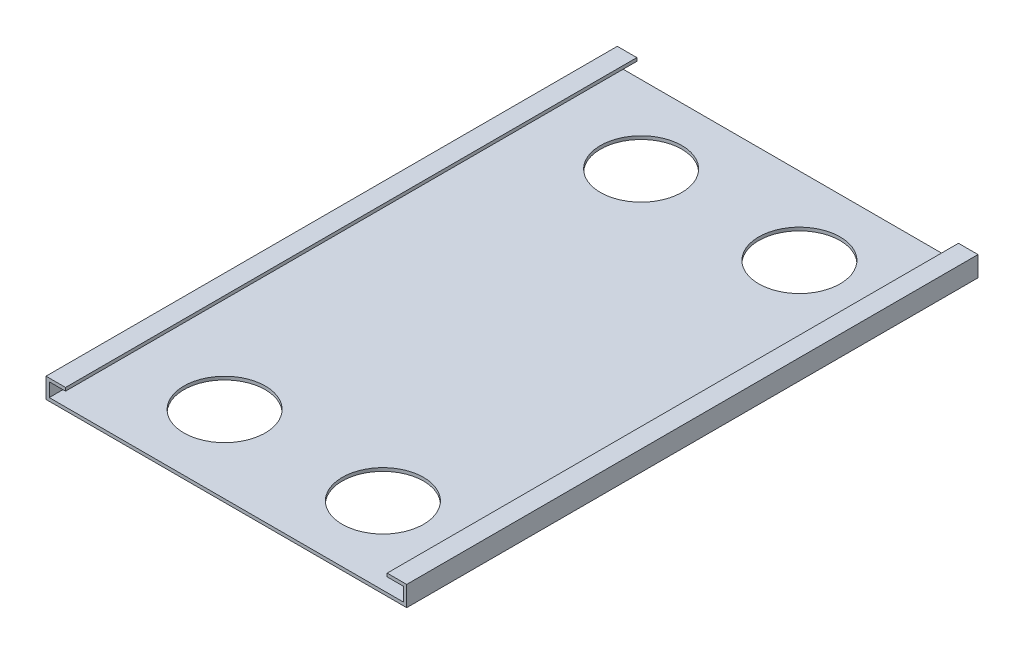
SolidWorks part; units mm, degrees
material "Thornel Mat VMA"
ref_plane "Front Plane" through (0, 0, 0) normal (0, 0, 1) x (1, 0, 0)
ref_plane "Top Plane" through (0, 0, 0) normal (0, 1, 0) x (1, 0, 0)
ref_plane "Right Plane" through (0, 0, 0) normal (1, 0, 0) x (0, 0, -1)
sketch "Sketch6" plane through (0, 0, 0) normal (0, 0, 1) x (1, 0, 0)
  line L0 (0, 23.8088) -> (0, -27.21) construction
  line L1 (36.0675, 0) -> (-36.7761, 0) construction
  line L2 (27.6352, 0) -> (-27.6352, 0)
  line L3 (-27.6352, 0) -> (-27.6352, 2.1336)
  line L4 (-27.6352, 2.1336) -> (-25.0952, 2.1336)
  line L5 (27.6352, 2.1336) -> (25.0952, 2.1336)
  line L6 (27.6352, 0) -> (27.6352, 2.1336)
  point P12 (0, 0)
  dimension "D1" = 27.6352
  dimension "D2" = 2.1336
  dimension "D3" = 2.54
extrude "Extrude-Thin3" add sketch "Sketch6" along normal blind 89.154 thin thin type one direction reverse wall 0.508
sketch "Sketch8" plane through (0, -0.508, 0) normal (0, -1, 0) x (1, 0, 0)
  line L0 (0, 127.0566) -> (0, -29.272) construction
  line L1 (-28.1432, 0) -> (28.1432, 89.154) construction
  line L2 (28.1432, 89.154) -> (28.1432, 0) construction
  line L3 (28.1432, 0) -> (-28.1432, 89.154) construction
  line L4 (0, 44.577) -> (87.2231, 44.577) construction
  line L5 (0, 44.577) -> (-86.0464, 44.577) construction
  line L6 (28.1432, 89.154) -> (-28.1432, 89.154) construction
  circle A4 centre (12.35, 77.077) radius 6.35
  circle A5 centre (-12.35, 77.077) radius 6.35
  circle A6 centre (-12.35, 12.077) radius 6.35
  circle A7 centre (12.35, 12.077) radius 6.35
  dimension "D1" = 12.7
  dimension "D2" = 24.7
  dimension "D3" = 65
extrude "Cut-Extrude1" cut sketch "Sketch8" against normal through all both and the other way through all
